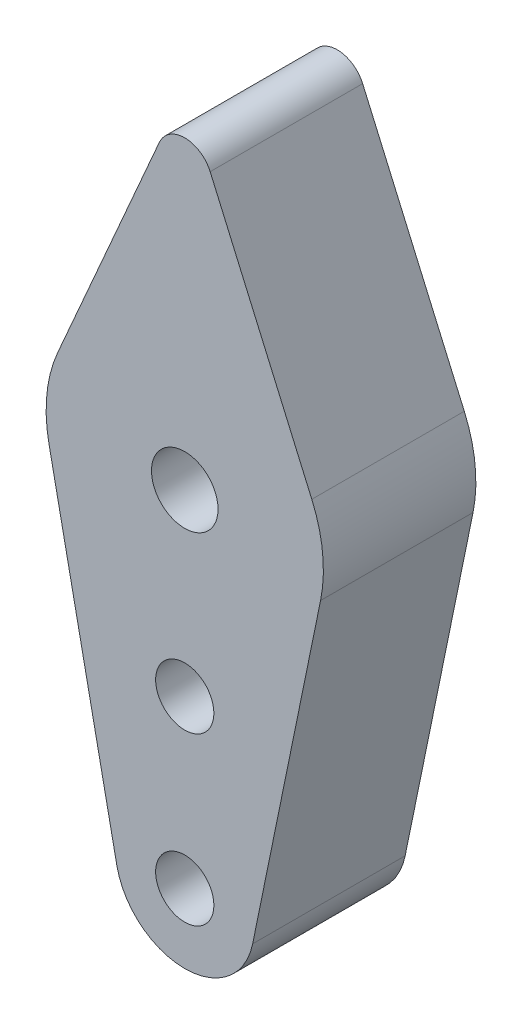
SolidWorks part; units mm, degrees
ref_plane "正面" through (0, 0, 0) normal (0, 0, 1) x (1, 0, 0)
ref_plane "平面" through (0, 0, 0) normal (0, 1, 0) x (1, 0, 0)
ref_plane "右側面" through (0, 0, 0) normal (1, 0, 0) x (0, 0, -1)
sketch "ｽｹｯﾁ1" plane through (0, 0, 0) normal (0, 0, 1) x (1, 0, 0)
  line L0 (-4.5826, 2) -> (-0.9165, 10.4)
  line L1 (4.5826, 2) -> (0.9165, 10.4)
  line L2 (-2.4491, -12.952) -> (-4.8982, -1.004)
  line L3 (2.4491, -12.952) -> (4.8982, -1.004)
  arc A0 (-4.5826, 2) -> (-4.8982, -1.004) centre (0, 0) ccw
  arc A1 (-2.4491, -12.952) -> (2.4491, -12.952) centre (0, -12.45) ccw
  circle A2 centre (0, -6.45) radius 1.05
  circle A3 centre (0, -12.45) radius 1.05
  arc A4 (-0.9165, 10.4) -> (0.9165, 10.4) centre (0, 10) cw
  circle A5 centre (0, 0) radius 1.2
  arc A7 (4.8982, -1.004) -> (4.5826, 2) centre (0, 0) ccw
  dimension "D1" = 12.45
  dimension "D2" = 2.5
  dimension "D3" = 2.1
  dimension "D5" = 10
  dimension "D6" = 1
  dimension "D7" = 10
  dimension "D8" = 2.4
  dimension "D4" = 6
extrude "ﾎﾞｽ - 押し出し1" add sketch "ｽｹｯﾁ1" along normal blind 5.5
